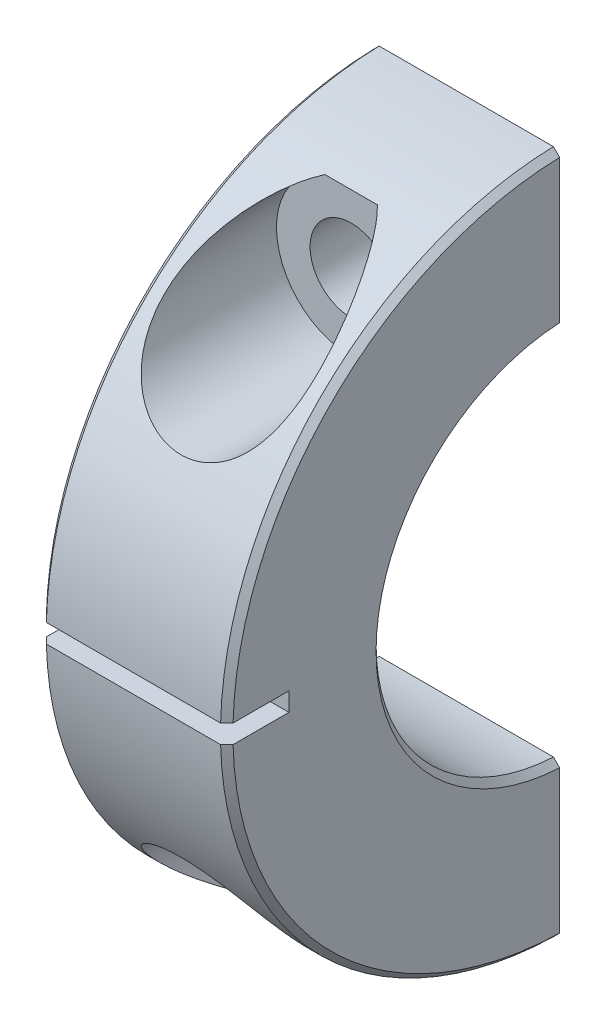
SolidWorks part; units mm, degrees
material "6061-O (SS)"
ref_plane "Front Plane" through (0, 0, 0) normal (0, 0, 1) x (1, 0, 0)
ref_plane "Top Plane" through (0, 0, 0) normal (0, 1, 0) x (1, 0, 0)
ref_plane "Right Plane" through (0, 0, 0) normal (1, 0, 0) x (0, 0, -1)
ref_plane "Plane1" through (-7.5, 0, 0) normal (-1, 0, 0) x (0, -1, 0)
sketch "Sketch1" plane through (-7.5, 0, 0) normal (-1, 0, 0) x (0, -1, 0)
  line L0 (-27.4898, 0.75) -> (27.4898, 0.75)
  arc A0 (27.4898, 0.75) -> (-27.4898, 0.75) centre (0, 0) ccw
extrude "Boss-Extrude1" add sketch "Sketch1" against normal blind 15
sketch "Sketch2" plane through (7.5, 0, 0) normal (1, 0, 0) x (0, 0, -1)
  line L0 (-27.4898, -0.75) -> (-22.5, -0.75)
  line L1 (-22.5, -0.75) -> (-22.5, 0.75)
  line L2 (-22.5, 0.75) -> (-27.4898, 0.75)
  arc A0 (-27.4898, 0.75) -> (-27.4898, -0.75) centre (0, 0) ccw
extrude "Cut-Extrude1" cut sketch "Sketch2" against normal through all
sketch "Sketch3" plane through (7.5, 0, 0) normal (1, 0, 0) x (0, 0, -1)
  line L0 (-0.75, -14.9812) -> (-0.75, 14.9812)
  arc A0 (-0.75, 14.9812) -> (-0.75, -14.9812) centre (0, 0) ccw
extrude "Cut-Extrude2" cut sketch "Sketch3" against normal through all
ref_plane "Plane2" through (0, 0, 23.6696) normal (0, 0, 1) x (1, 0, 0)
hole_wizard "CBORE for M6 Hex Head Bolt1" positions "Sketch5" profile "Sketch4" counterbore size "M6" standard "ANSI Metric"
sketch "Sketch5" plane through (0, 0, 23.6696) normal (0, 0, 1) x (1, 0, 0)
  point P0 (0, -20)
  point P1 (0, 20)
sketch "Sketch4" plane through (0, -20, 23.6696) normal (1, 0, 0) x (0, -1, 0)
  line L0 (0, 0) -> (0, 22.9196)
  line L1 (0, 22.9196) -> (3.3, 22.9196)
  line L3 (3.3, 22.9196) -> (3.3, 13.6696)
  line L4 (3.3, 13.6696) -> (6, 13.6696)
  line L5 (6, 13.6696) -> (6, 0)
  line L7 (6, 0) -> (0, 0)
  line L11 (0, -6.35) -> (0, 107.95) construction
  dimension "Thru Hole Dia." = 6.6
  dimension "Thru Hole Depth" = 22.9196
  dimension "C'Bore Dia." = 12
  dimension "C'Bore Depth" = 13.6696
chamfer "Chamfer1" distance 0.5 angle 45 6 edges at (7.5, -19.4454, 19.4454) (7.5, 19.4454, 19.4454) (7.5, 0, 15) (-7.5, 19.4454, 19.4454) (-7.5, -19.4454, 19.4454) (-7.5, 0, 15)
